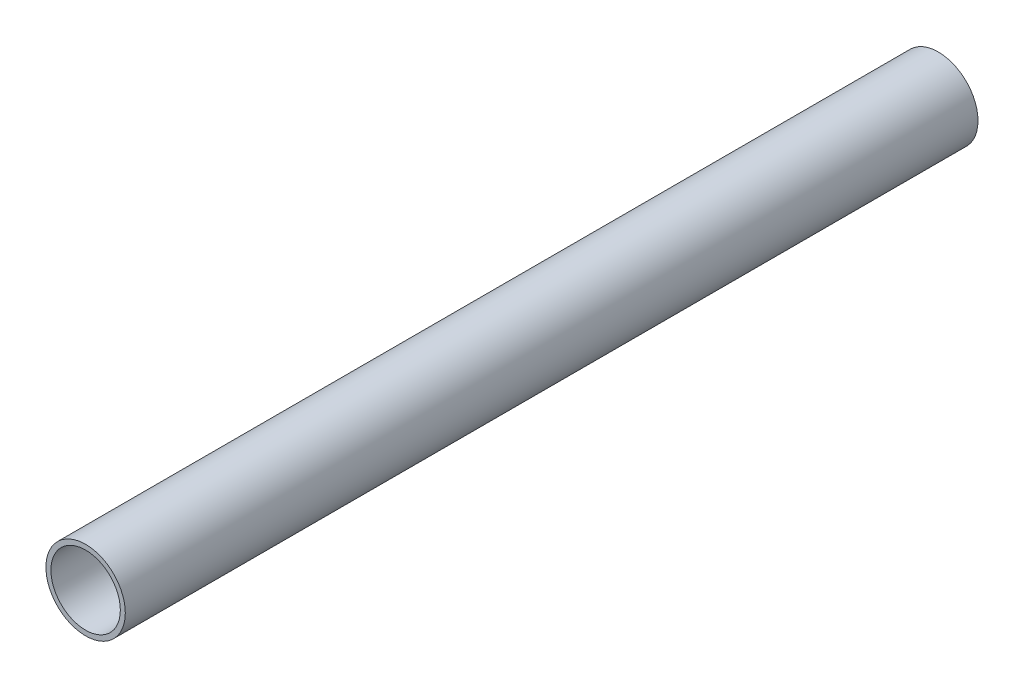
SolidWorks part; units mm, degrees
material "PC High Viscosity"
ref_plane "Front Plane" through (0, 0, 0) normal (0, 0, 1) x (1, 0, 0)
ref_plane "Top Plane" through (0, 0, 0) normal (0, 1, 0) x (1, 0, 0)
ref_plane "Right Plane" through (0, 0, 0) normal (1, 0, 0) x (0, 0, -1)
sketch "Sketch1" plane through (0, 0, 0) normal (0, 0, 1) x (1, 0, 0)
  circle A0 centre (0, 0) radius 12.7
  circle A1 centre (0, 0) radius 11.1125
  dimension "D1" = 25.4
  dimension "D2" = 1.5875
extrude "Boss-Extrude1" add sketch "Sketch1" along normal blind 272.89
